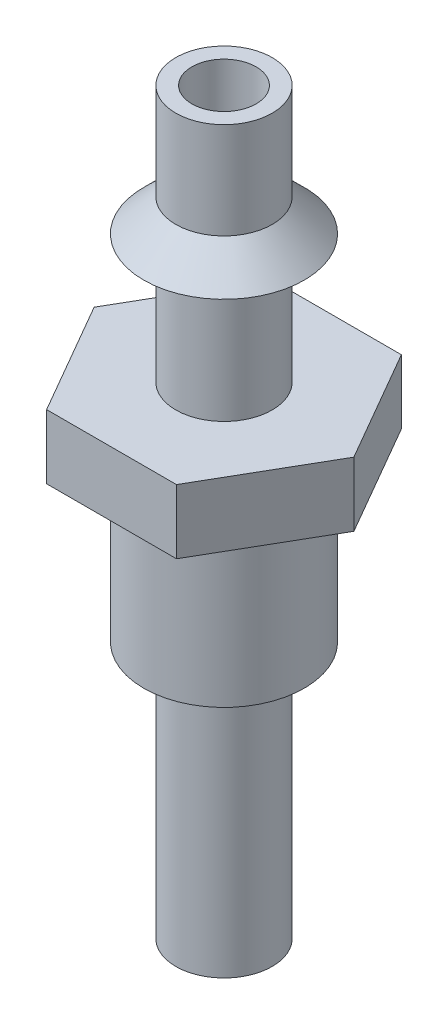
SolidWorks part; units mm, degrees
ref_plane "Front Plane" through (0, 0, 0) normal (0, 0, 1) x (1, 0, 0)
ref_plane "Top Plane" through (0, 0, 0) normal (0, 1, 0) x (1, 0, 0)
ref_plane "Right Plane" through (0, 0, 0) normal (1, 0, 0) x (0, 0, -1)
sketch "Sketch1" plane through (0, 0, 0) normal (0, 1, 0) x (1, 0, 0)
  circle A0 centre (0, 0) radius 1.5
  dimension "D1" = 3
extrude "Boss-Extrude1" add sketch "Sketch1" along normal blind 23
sketch "Sketch2" plane through (0, 0, 0) normal (0, 1, 0) x (1, 0, 0)
  circle A0 centre (0, 0) radius 2.5
  dimension "D1" = 5
extrude "Boss-Extrude2" add sketch "Sketch2" along normal blind 5 from offset 8
sketch "Sketch3" plane through (0, 13, 0) normal (0, 1, 0) x (1, 0, 0)
  line L1 (-2.0207, 3.5) -> (-4.0415, 0)
  line L2 (-4.0415, 0) -> (-2.0207, -3.5)
  line L3 (-2.0207, -3.5) -> (2.0207, -3.5)
  line L4 (2.0207, -3.5) -> (4.0415, 0)
  line L5 (4.0415, 0) -> (2.0207, 3.5)
  line L6 (2.0207, 3.5) -> (-2.0207, 3.5)
  circle A0 centre (0, 0) radius 3.5 construction
  point P1 (0, -3.5)
  dimension "D1" = 7
extrude "Boss-Extrude3" add sketch "Sketch3" along normal blind 2
sketch "Sketch5" plane through (0, 15, 0) normal (0, 1, 0) x (1, 0, 0)
  circle A0 centre (0, 0) radius 2.5
  dimension "D1" = 5
extrude "Boss-Extrude4" add sketch "Sketch5" along normal blind 1 draft 45 from offset 4
sketch "Sketch6" plane through (0, 0, 0) normal (0, -1, 0) x (1, 0, 0)
  circle A0 centre (0, 0) radius 1
  dimension "D1" = 2
extrude "Cut-Extrude1" cut sketch "Sketch6" against normal through all both and the other way through all
